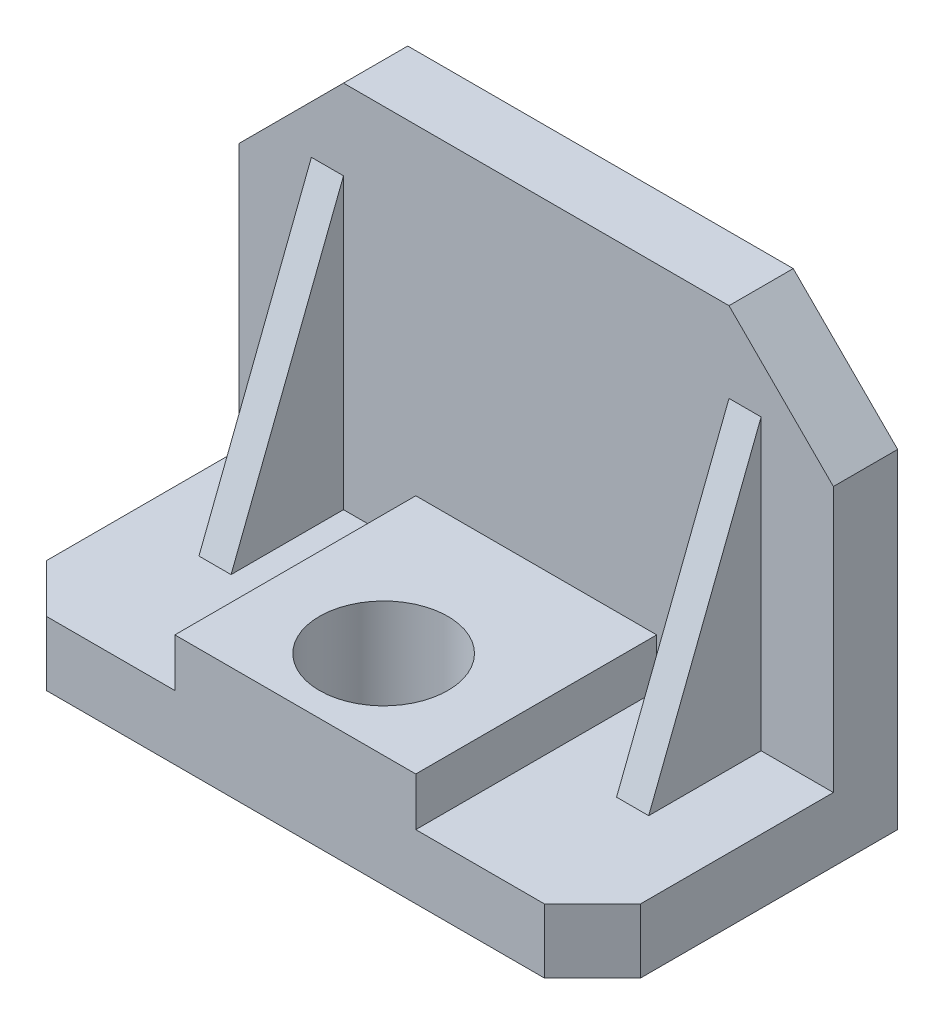
SolidWorks part; units mm, degrees
ref_plane "Front Plane" through (0, 0, 0) normal (0, 0, 1) x (1, 0, 0)
ref_plane "Top Plane" through (0, 0, 0) normal (0, 1, 0) x (1, 0, 0)
ref_plane "Right Plane" through (0, 0, 0) normal (1, 0, 0) x (0, 0, -1)
sketch "Sketch1" plane through (0, 0, 0) normal (0, 0, 1) x (1, 0, 0)
  line L0 (-74, 0) -> (-74, 41)
  line L1 (-74, 41) -> (-61, 54)
  line L2 (-61, 54) -> (-13, 54)
  line L3 (-13, 54) -> (0, 41)
  line L4 (0, 41) -> (0, 0)
  line L5 (0, 0) -> (-74, 0)
  dimension "D1" = 48
  dimension "D2" = 13
  dimension "D3" = 13
  dimension "D4" = 41
  dimension "D5" = 13
  dimension "D6" = 13
extrude "Boss-Extrude4" add sketch "Sketch1" along normal mid plane 8
sketch "Sketch5" plane through (0, 0, 4) normal (0, 0, 1) x (1, 0, 0)
  line L1 (-74, 0) -> (0, 0)
  line L2 (-74, 0) -> (-74, 8)
  line L3 (-74, 8) -> (0, 8)
  line L4 (0, 0) -> (0, 8)
  dimension "D1" = 8
extrude "Boss-Extrude5" add sketch "Sketch5" along normal blind 30
sketch "Sketch6" plane through (0, 0, 0) normal (0, 0, 1) x (1, 0, 0)
  line L0 (0, 8) -> (-74, 8) construction
  line L1 (-65, 44) -> (-61, 44)
  line L2 (-65, 44) -> (-65, 8)
  line L3 (-65, 8) -> (-61, 8)
  line L4 (-61, 44) -> (-61, 8)
  line L5 (0, 8) -> (-74, 8) construction
  line L6 (-13, 44) -> (-9, 44)
  line L7 (-13, 44) -> (-13, 8)
  line L8 (-13, 8) -> (-9, 8)
  line L9 (-9, 44) -> (-9, 8)
  line L10 (0, 8) -> (0, 41) construction
  line L11 (-74, 41) -> (-74, 8) construction
  dimension "D1" = 36
  dimension "D2" = 36
  dimension "D3" = 4
  dimension "D4" = 4
  dimension "D5" = 9
  dimension "D6" = 9
extrude "Boss-Extrude6" add sketch "Sketch6" along normal blind 18
sketch "Sketch8" plane through (0, 8, 0) normal (0, 1, 0) x (1, 0, 0)
  line L0 (-74, -28) -> (-67.9965, -34)
  line L1 (-74, -34) -> (-74, -4) construction
  line L2 (0, -34) -> (-74, -34) construction
  line L3 (-67.9965, -34) -> (-74, -34)
  line L4 (-74, -34) -> (-74, -28)
  line L5 (0, -34) -> (-6, -34)
  line L6 (-6, -34) -> (0, -28)
  line L7 (0, -34) -> (0, -4) construction
  line L8 (0, -28) -> (0, -34)
  dimension "D1" = 6.0035
  dimension "D2" = 6
  dimension "D3" = 6
  dimension "D4" = 6
extrude "Cut-Extrude2" cut sketch "Sketch8" against normal blind 18
sketch "Sketch9" plane through (0, 8, 0) normal (0, 1, 0) x (1, 0, 0)
  line L0 (-13, -4) -> (-61, -4) construction
  line L1 (-52, -4) -> (-22, -4)
  line L2 (-52, -4) -> (-52, -34)
  line L3 (-52, -34) -> (-22, -34)
  line L4 (-22, -4) -> (-22, -34)
  line L5 (-6, -34) -> (-67.9965, -34) construction
  line L6 (0, -28) -> (0, -4) construction
  dimension "D1" = 30
  dimension "D2" = 22
extrude "Boss-Extrude11" add sketch "Sketch9" along normal blind 6
sketch "Sketch10" plane through (0, 14, 0) normal (0, 1, 0) x (1, 0, 0)
  line L0 (-52, -34) -> (-22, -34) construction
  line L1 (-22, -34) -> (-22, -4) construction
  circle A0 centre (-37, -23) radius 8
  dimension "D2" = 16
  dimension "D3" = 15
  dimension "D1" = 11
extrude "Cut-Extrude3" cut sketch "Sketch10" against normal blind 50
sketch "Sketch11" plane through (-9, 0, 0) normal (1, 0, 0) x (0, 0, -1)
  line L0 (-4, 44) -> (-18, 8)
  line L1 (-18, 8) -> (-18, 44)
  line L2 (-18, 44) -> (-4, 44)
extrude "Cut-Extrude4" cut sketch "Sketch11" against normal blind 8
sketch "Sketch12" plane through (-61, 0, 0) normal (1, 0, 0) x (0, 0, -1)
  line L0 (-4, 44) -> (-18, 8)
  line L1 (-18, 8) -> (-18, 44)
  line L2 (-18, 44) -> (-4, 44)
  line L4 (-4, 8) -> (-4, 44) construction
  point P0 (-18, 44)
  point P2 (-3.0319, 42.3143)
  point P5 (-4.4844, 43.1255)
  point P6 (18.6957, 42.3437)
  dimension "D1" = 36
extrude "Cut-Extrude5" cut sketch "Sketch12" against normal blind 8
